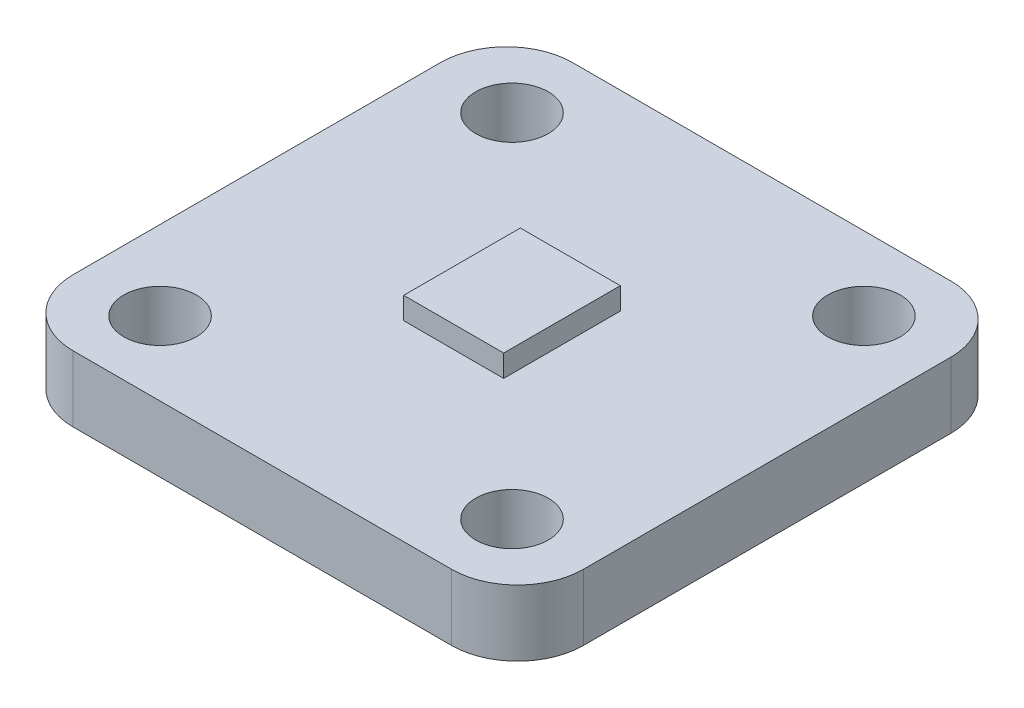
SolidWorks part; units mm, degrees
ref_plane "前视基准面" through (0, 0, 0) normal (0, 0, 1) x (1, 0, 0)
ref_plane "上视基准面" through (0, 0, 0) normal (0, 1, 0) x (1, 0, 0)
ref_plane "右视基准面" through (0, 0, 0) normal (1, 0, 0) x (0, 0, -1)
sketch "草图1" plane through (0, 0, 0) normal (0, 1, 0) x (1, 0, 0)
  line L1 (-11.6, 11.35) -> (11.6, 11.35)
  line L2 (-11.6, 11.35) -> (-11.6, -11.35)
  line L3 (-11.6, -11.35) -> (11.6, -11.35)
  line L4 (11.6, 11.35) -> (11.6, -11.35)
  line L5 (-11.6, 11.35) -> (11.6, -11.35) construction
  line L6 (-11.6, -11.35) -> (11.6, 11.35) construction
  line L7 (-8, 8) -> (8, 8) construction
  line L8 (-8, 8) -> (-8, -8) construction
  line L9 (-8, -8) -> (8, -8) construction
  line L10 (8, 8) -> (8, -8) construction
  line L11 (-8, 8) -> (8, -8) construction
  line L12 (-8, -8) -> (8, 8) construction
  circle A0 centre (-8, 8) radius 1.65
  circle A1 centre (8, 8) radius 1.65
  circle A2 centre (8, -8) radius 1.65
  circle A3 centre (-8, -8) radius 1.65
  point P0 (0, 0)
  point P6 (0, 0)
  dimension "D5" = 3.3
  dimension "D1" = 16
  dimension "D2" = 16
  dimension "D3" = 23.2
  dimension "D4" = 22.7
extrude "凸台-拉伸1" add sketch "草图1" along normal blind 3
fillet "圆角1" radius 3 4 edges at (-11.6, 1.5, -11.35) (11.6, 1.5, -11.35) (11.6, 1.5, 11.35) (-11.6, 1.5, 11.35)
sketch "草图2" plane through (0, 3, 0) normal (0, 1, 0) x (1, 0, 0)
  line L1 (-2.272, 2.6506) -> (2.272, 2.6506)
  line L2 (-2.272, 2.6506) -> (-2.272, -2.6506)
  line L3 (-2.272, -2.6506) -> (2.272, -2.6506)
  line L4 (2.272, 2.6506) -> (2.272, -2.6506)
  line L5 (-2.272, 2.6506) -> (2.272, -2.6506) construction
  line L6 (-2.272, -2.6506) -> (2.272, 2.6506) construction
  point P0 (0, 0)
  point P6 (2.272, 2.6506)
extrude "凸台-拉伸2" add sketch "草图2" along normal blind 1
